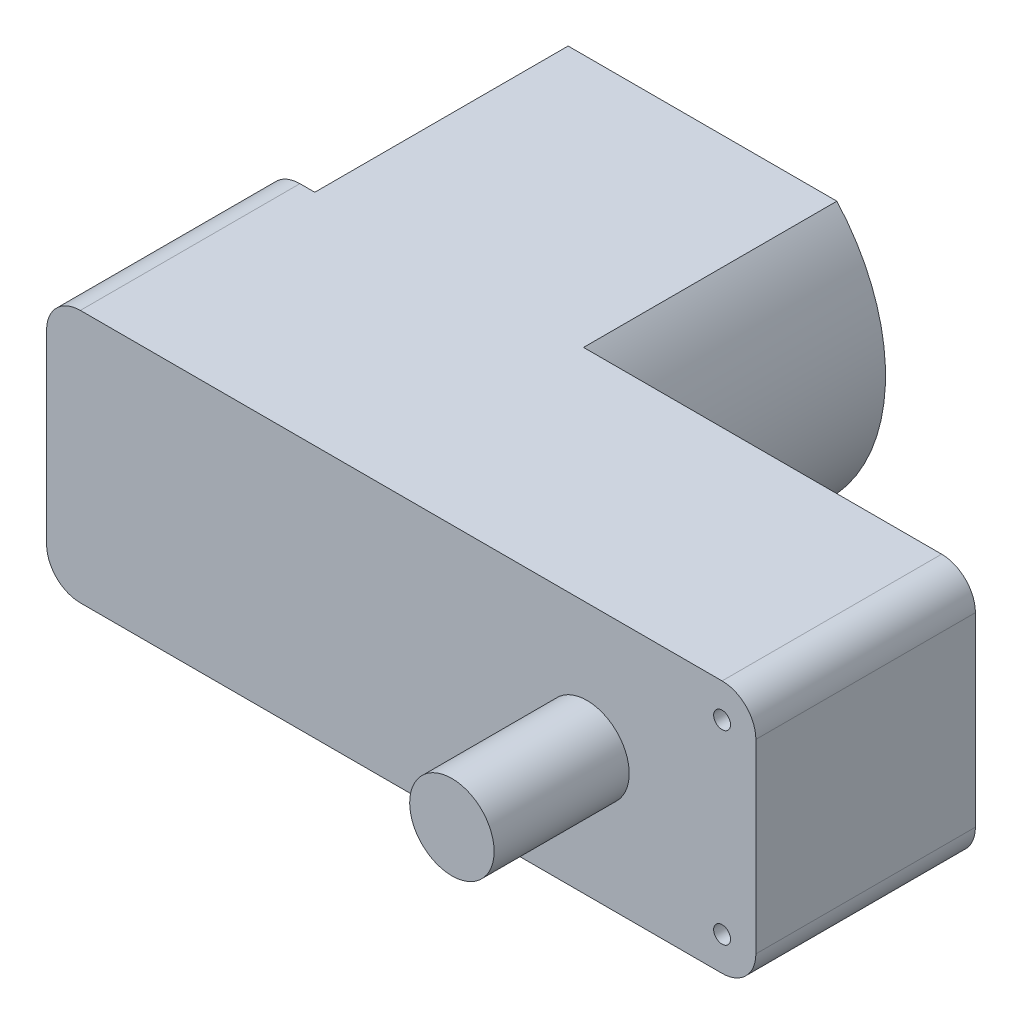
SolidWorks part; units mm, degrees
ref_plane "Front Plane" through (0, 0, 0) normal (0, 0, 1) x (1, 0, 0)
ref_plane "Top Plane" through (0, 0, 0) normal (0, 1, 0) x (1, 0, 0)
ref_plane "Right Plane" through (0, 0, 0) normal (1, 0, 0) x (0, 0, -1)
sketch "Sketch1" plane through (0, 0, 0) normal (0, 0, 1) x (1, 0, 0)
  line L0 (0, 0) -> (0, 6.5) construction
  line L1 (-7.5, -6.5) -> (7.5, -6.5)
  line L2 (-7.5, -6.5) -> (-7.5, 6.5)
  line L3 (-7.5, 6.5) -> (7.5, 6.5)
  line L4 (7.5, -6.5) -> (7.5, 6.5)
  line L5 (-7.5, -6.5) -> (7.5, 6.5) construction
  line L6 (-7.5, 6.5) -> (7.5, -6.5) construction
  line L7 (-7.9574, -7.5) -> (7.9574, -7.5)
  line L8 (-7.9574, 7.5) -> (7.9574, 7.5)
  arc A0 (-7.5, 6.5) -> (-7.5, -6.5) centre (0.3607, 0) ccw
  arc A1 (7.5, 6.5) -> (7.5, -6.5) centre (-0.3607, 0) cw
  arc A2 (-7.9574, 7.5) -> (-7.9574, -7.5) centre (0.3607, 0) ccw
  arc A3 (7.9574, 7.5) -> (7.9574, -7.5) centre (-0.3607, 0) cw
  point P0 (0, 0)
  dimension "D3" = 1
  dimension "D1" = 15
  dimension "D2" = 13
extrude "Boss-Extrude1" add sketch "Sketch1" along normal blind 15 contours A3 L8 A2 L7 L3 A1 L1 A0
sketch "Sketch2" plane through (0, 0, 15) normal (0, 0, 1) x (1, 0, 0)
  line L0 (-7.9574, 7.5) -> (-14.5178, 7.5) construction
  line L1 (-10.8393, 0) -> (-10.8393, 8.3214) construction
  line L2 (-10.8393, 7.5) -> (-10.8393, -7.5)
  line L3 (-10.8393, 7.5) -> (31.1607, 7.5)
  line L4 (-10.8393, -7.5) -> (31.1607, -7.5)
  line L5 (31.1607, 7.5) -> (31.1607, -7.5)
  arc A0 (-7.9574, 7.5) -> (-7.9574, -7.5) centre (0.3607, 0) ccw construction
  dimension "D1" = 15
  dimension "D2" = 42
extrude "Boss-Extrude2" add sketch "Sketch2" along normal blind 13
fillet "Fillet1" radius 2 4 edges at (-10.8393, 7.5, 21.5) (-10.8393, -7.5, 21.5) (31.1607, -7.5, 21.5) (31.1607, 7.5, 21.5)
sketch "Sketch3" plane through (0, 0, 28) normal (0, 0, 1) x (1, 0, 0)
  line L0 (31.1607, -5.5) -> (31.1607, 5.5) construction
  line L1 (0, 0) -> (37.8029, 0) construction
  circle A0 centre (21.1607, 0) radius 2.5
  dimension "D1" = 10
extrude "Boss-Extrude3" add sketch "Sketch3" along normal blind 8
sketch "Sketch4" plane through (0, 0, 28) normal (0, 0, 1) x (1, 0, 0)
  line L0 (0, 0) -> (43.4766, 0) construction
  line L1 (31.1607, -5.5) -> (31.1607, 5.5) construction
  line L2 (29.1607, 7.5) -> (-8.8393, 7.5) construction
  circle A0 centre (29.1607, 5.5) radius 0.5
  point P5 (0, 0)
  point P6 (0, 0)
  point P10 (0, 0)
  point P12 (29.1607, 7.5)
  dimension "D1" = 1
  dimension "D2" = 2
  dimension "D3" = 2
extrude "Cut-Extrude1" cut sketch "Sketch4" against normal through all
ref_plane "Plane1" through (0, 0, 0) normal (0, 1, 0) x (1, 0, 0)
mirror "Mirror1" about plane through (0, 0, 0) normal (0, 1, 0) of "Cut-Extrude1"
